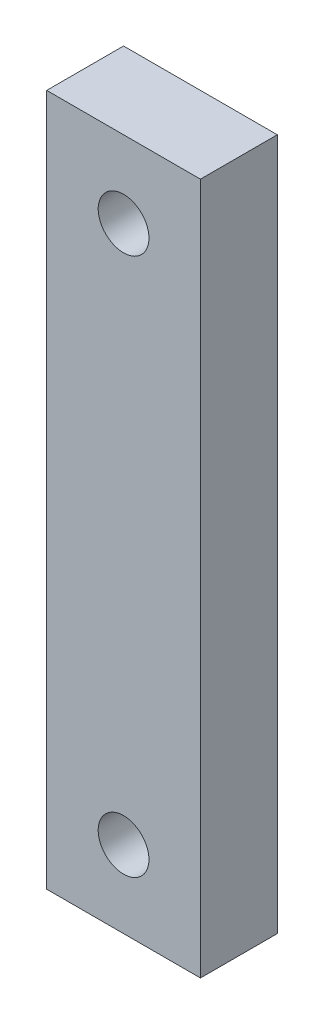
SolidWorks part; units mm, degrees
ref_plane "前视基准面" through (0, 0, 0) normal (0, 0, 1) x (1, 0, 0)
ref_plane "上视基准面" through (0, 0, 0) normal (0, 1, 0) x (1, 0, 0)
ref_plane "右视基准面" through (0, 0, 0) normal (1, 0, 0) x (0, 0, -1)
other "Configuration Table"
sketch "草图1" plane through (0, 0, 0) normal (0, 0, 1) x (1, 0, 0)
  line L1 (-5, 22.5) -> (5, 22.5)
  line L2 (-5, 22.5) -> (-5, -22.5)
  line L3 (-5, -22.5) -> (5, -22.5)
  line L4 (5, 22.5) -> (5, -22.5)
  line L5 (-5, 22.5) -> (5, -22.5) construction
  line L6 (-5, -22.5) -> (5, 22.5) construction
  circle A0 centre (0, 17.5) radius 1.65
  circle A1 centre (0, -17.5) radius 1.65
  point P0 (0, 0)
  dimension "D3" = 5
  dimension "D4" = 35
  dimension "D5" = 3.3
  dimension "D6" = 3.3
  dimension "D1" = 45
  dimension "D2" = 10
extrude "凸台-拉伸1" add sketch "草图1" along normal blind 5
